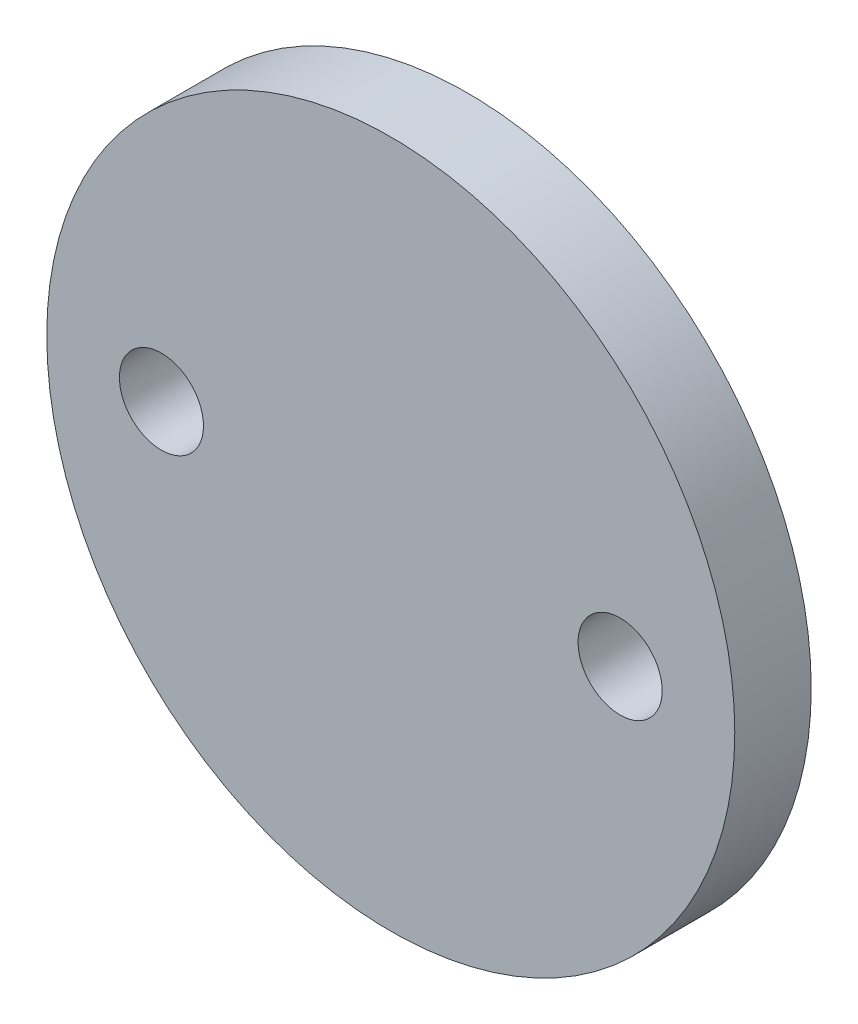
SolidWorks part; units mm, degrees
ref_plane "前视基准面" through (0, 0, 0) normal (0, 0, 1) x (1, 0, 0)
ref_plane "上视基准面" through (0, 0, 0) normal (0, 1, 0) x (1, 0, 0)
ref_plane "右视基准面" through (0, 0, 0) normal (1, 0, 0) x (0, 0, -1)
sketch "草图1" plane through (0, 0, 0) normal (0, 0, 1) x (1, 0, 0)
  line L0 (-14.8848, 0) -> (-2.8848, 0) construction
  circle A0 centre (-14.8848, 0) radius 1.1
  circle A1 centre (-2.8848, 0) radius 1.1
  circle A2 centre (-8.8848, 0) radius 9
extrude "凸台-拉伸1" add sketch "草图1" along normal blind 2
